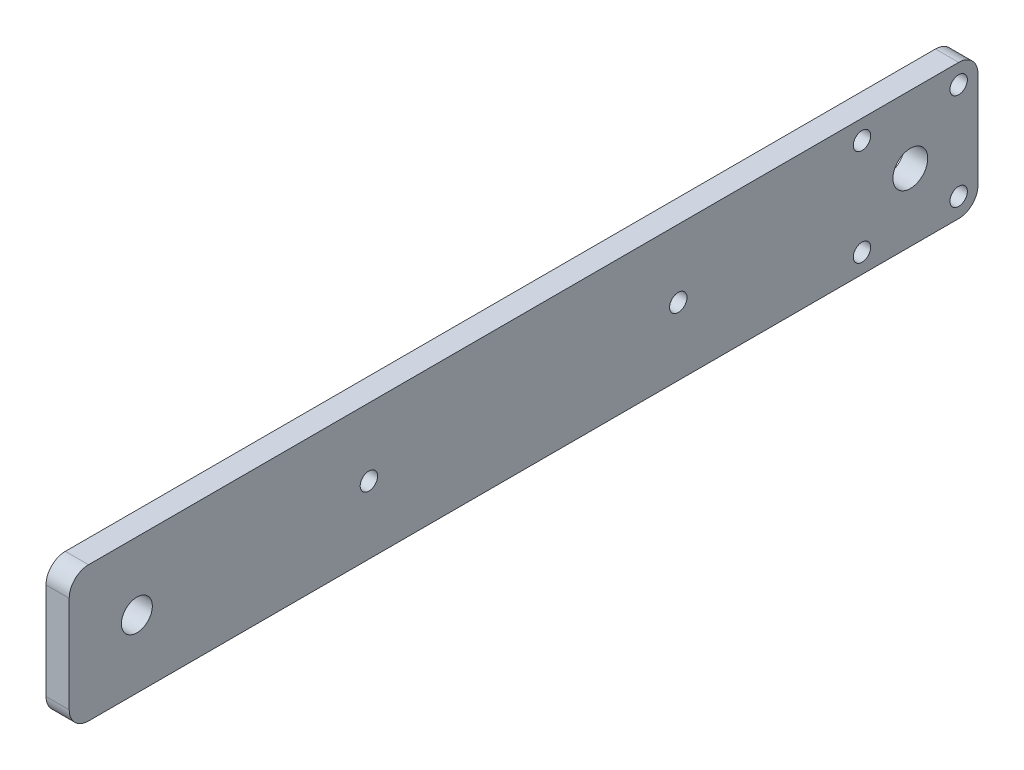
SolidWorks part; units mm, degrees
material "6061-T6 (SS)"
ref_plane "Alzado" through (0, 0, 0) normal (0, 0, 1) x (1, 0, 0)
ref_plane "Planta" through (0, 0, 0) normal (0, 1, 0) x (1, 0, 0)
ref_plane "Vista lateral" through (0, 0, 0) normal (1, 0, 0) x (0, 0, -1)
sketch "Croquis2" plane through (0, 0, 0) normal (1, 0, 0) x (0, 0, -1)
  line L2 (-100, 0) -> (100, 0) construction
  line L3 (-117.5, 17.5) -> (117.5, 17.5)
  line L4 (-117.5, 17.5) -> (-117.5, -17.5)
  line L5 (117.5, 17.5) -> (117.5, -17.5)
  line L6 (117.5, -17.5) -> (-117.5, -17.5)
  circle A2 centre (-100, 0) radius 4
  circle A3 centre (100, 0) radius 4.5
  point P3 (-117.5, 0)
  point P4 (0, 0)
  point P7 (0, 17.5)
  dimension "D1" = 8
  dimension "D2" = 200
  dimension "D6" = 9
  dimension "D3" = 35
  dimension "D4" = 17.5
extrude "Saliente-Extruir1" add sketch "Croquis2" along normal mid plane 6
fillet "Redondeo1" radius 5 4 edges at (0, -17.5, -117.5) (0, 17.5, -117.5) (0, -17.5, 117.5) (0, 17.5, 117.5)
hole_wizard "Taladro de margen para M41" positions "Croquis9" profile "Croquis8" hole size "M4" standard "Ansi Metric" end condition up to next
sketch "Croquis9" plane through (3, 0, 0) normal (1, 0, 0) x (0, 0, -1)
  point P2 (112.5, 12.5)
  point P5 (87.5, 12.5)
  point P8 (87.5, -12.5)
  point P11 (112.5, -12.5)
sketch "Croquis8" plane through (3, 12.5, -112.5) normal (0, 1, 0) x (0, 0, -1)
  line L0 (0, 0) -> (0, 6)
  line L1 (0, 6) -> (2.25, 6)
  line L2 (2.25, 6) -> (2.25, 0)
  line L5 (2.25, 0) -> (0, 0)
  line L11 (0, -6.35) -> (0, 107.95) construction
  dimension "Diámetro de taladro hasta el siguiente" = 4.5
  dimension "Profundidad de taladro hasta el siguiente" = 6
hole_wizard "Taladro de margen para M42" positions "Croquis10" profile "Croquis11" hole size "M4" standard "Ansi Metric" end condition up to next
sketch "Croquis10" plane through (3, 0, 0) normal (1, 0, 0) x (0, 0, -1)
  line L2 (-40, 0) -> (40, 0) construction
  point P0 (-40, 0)
  point P2 (40, 0)
  point P14 (0, 0)
  dimension "D1" = 80
sketch "Croquis11" plane through (3, 0, 40) normal (0, 1, 0) x (0, 0, -1)
  line L0 (0, 0) -> (0, 6)
  line L1 (0, 6) -> (2.25, 6)
  line L2 (2.25, 6) -> (2.25, 0)
  line L5 (2.25, 0) -> (0, 0)
  line L11 (0, -6.35) -> (0, 107.95) construction
  dimension "Diámetro de taladro hasta el siguiente" = 4.5
  dimension "Profundidad de taladro hasta el siguiente" = 6
